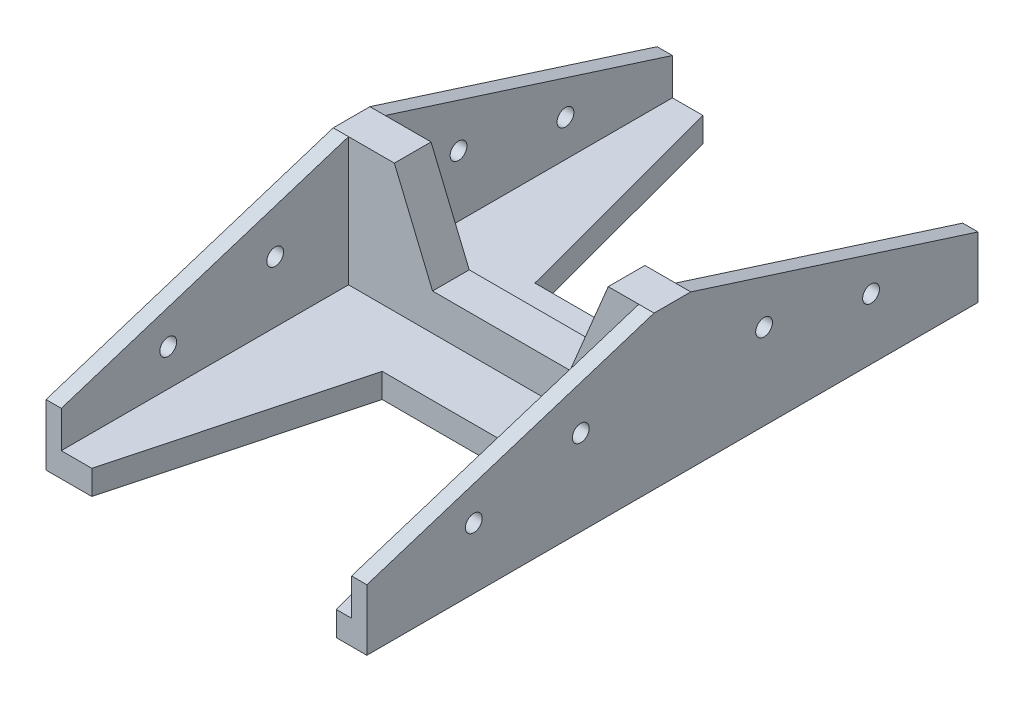
SolidWorks part; units mm, degrees
ref_plane "前视基准面" through (0, 0, 0) normal (0, 0, 1) x (1, 0, 0)
ref_plane "上视基准面" through (0, 0, 0) normal (0, 1, 0) x (1, 0, 0)
ref_plane "右视基准面" through (0, 0, 0) normal (1, 0, 0) x (0, 0, -1)
sketch "草图1" plane through (0, 0, 0) normal (1, 0, 0) x (0, 0, -1)
  line L0 (6, 0) -> (100, 0)
  line L1 (-100, 0) -> (-6, 0)
  line L2 (-100, 0) -> (-100, -20)
  line L3 (-100, -20) -> (100, -20)
  line L4 (100, 0) -> (100, -20)
  line L5 (-6, 30) -> (6, 30)
  line L6 (-6, 30) -> (-6, 0)
  line L8 (6, 30) -> (6, 0)
  dimension "D1" = 100
  dimension "D2" = 100
  dimension "D3" = 30
  dimension "D4" = 20
  dimension "D5" = 12
  dimension "D6" = 6
extrude "凸台-拉伸1" add sketch "草图1" along normal blind 5
sketch "草图2" plane through (5, 0, 0) normal (1, 0, 0) x (0, 0, -1)
  line L0 (-6, -12) -> (-6, 30)
  line L1 (-6, 30) -> (6, 30)
  line L2 (6, 30) -> (6, -12)
  line L3 (6, -12) -> (100, -12)
  line L4 (100, -20) -> (100, 0) construction
  line L5 (100, -12) -> (100, -20)
  line L6 (100, -20) -> (-100, -20)
  line L7 (-100, -20) -> (-100, -12)
  line L8 (-100, 0) -> (-100, -20) construction
  line L9 (-100, -12) -> (-6, -12)
  dimension "D1" = 8
  dimension "D2" = 8
extrude "凸台-拉伸2" add sketch "草图2" along normal blind 100
sketch "草图3" plane through (0, -12, 0) normal (0, 1, 0) x (1, 0, 0)
  line L0 (15, 100) -> (35, 25)
  line L1 (105, 100) -> (5, 100) construction
  line L5 (55, 6) -> (55, 50006) construction
  line L6 (105, 6) -> (5, 6) construction
  line L7 (15, 100) -> (95, 100)
  line L8 (35, 25) -> (75, 25)
  line L9 (95, 100) -> (75, 25)
  line L10 (0, 0) -> (50000, 0) construction
  line L11 (15, -100) -> (35, -25)
  line L12 (95, -100) -> (75, -25)
  line L13 (35, -25) -> (75, -25)
  line L14 (15, -100) -> (95, -100)
  point P10 (55, 6)
  point P12 (55, 25)
  point P13 (55, 100)
  dimension "D1" = 20
  dimension "D2" = 40
  dimension "D3" = 75
extrude "切除-拉伸1" cut sketch "草图3" against normal blind 100
sketch "草图5" plane through (0, 0, 6) normal (0, 0, 1) x (1, 0, 0)
  line L0 (20, 30) -> (32.5, 0)
  line L1 (105, 30) -> (0, 30) construction
  line L2 (32.5, 0) -> (77.5, 0)
  line L3 (55, -12) -> (55, 49988) construction
  line L4 (75, -12) -> (35, -12) construction
  line L5 (20, 30) -> (90, 30)
  line L6 (90, 30) -> (77.5, 0)
  point P6 (55, 30)
  point P11 (55, -12)
  point P13 (55, 0)
  dimension "D1" = 30
  dimension "D2" = 45
  dimension "D3" = 70
extrude "切除-拉伸2" cut sketch "草图5" against normal blind 100
sketch "草图6" plane through (5, 0, 0) normal (1, 0, 0) x (0, 0, -1)
  line L0 (-100, 0) -> (-6, 30)
  line L1 (-6, 30) -> (-6, 0)
  line L2 (-6, 0) -> (-100, 0)
  line L3 (0, 30) -> (0, 50030) construction
  line L4 (6, 30) -> (-6, 30) construction
  line L5 (6, 0) -> (100, 0)
  line L6 (6, 30) -> (6, 0)
  line L7 (100, 0) -> (6, 30)
  point P10 (0, 30)
extrude "凸台-拉伸3" add sketch "草图6" against normal blind 5
sketch "草图7" plane through (105, 0, 0) normal (1, 0, 0) x (0, 0, -1)
  line L4 (6, 30) -> (6, -12)
  line L5 (6, -12) -> (100, -12)
  line L6 (100, -12) -> (100, 0)
  line L7 (100, 0) -> (6, 30)
  line L8 (6, 30) -> (6, -12)
  line L9 (6, -12) -> (100, -12)
  line L10 (100, -12) -> (100, 0)
  line L11 (100, 0) -> (6, 30)
  line L12 (-100, -12) -> (-6, -12)
  line L13 (-6, -12) -> (-6, 30)
  line L14 (-6, 30) -> (-100, 0)
  line L15 (-100, 0) -> (-100, -12)
  line L16 (-100, -12) -> (-6, -12)
  line L17 (-6, -12) -> (-6, 30)
  line L18 (-6, 30) -> (-100, 0)
  line L19 (-100, 0) -> (-100, -12)
  dimension "D1" = 0
  dimension "D2" = 0
extrude "凸台-拉伸4" add sketch "草图7" against normal blind 5
sketch "草图9" plane through (105, 0, 0) normal (1, 0, 0) x (0, 0, -1)
  line L0 (0, 0) -> (0, 50000) construction
  circle A1 centre (30, 8) radius 2.75
  circle A2 centre (65, 0) radius 2.75
  circle A3 centre (-65, 0) radius 2.75
  circle A4 centre (-30, 8) radius 2.75
  dimension "D1" = 30
  dimension "D4" = 5.5
  dimension "D5" = 5.5
  dimension "D2" = 8
  dimension "D3" = 65
extrude "切除-拉伸3" cut sketch "草图9" against normal through all
